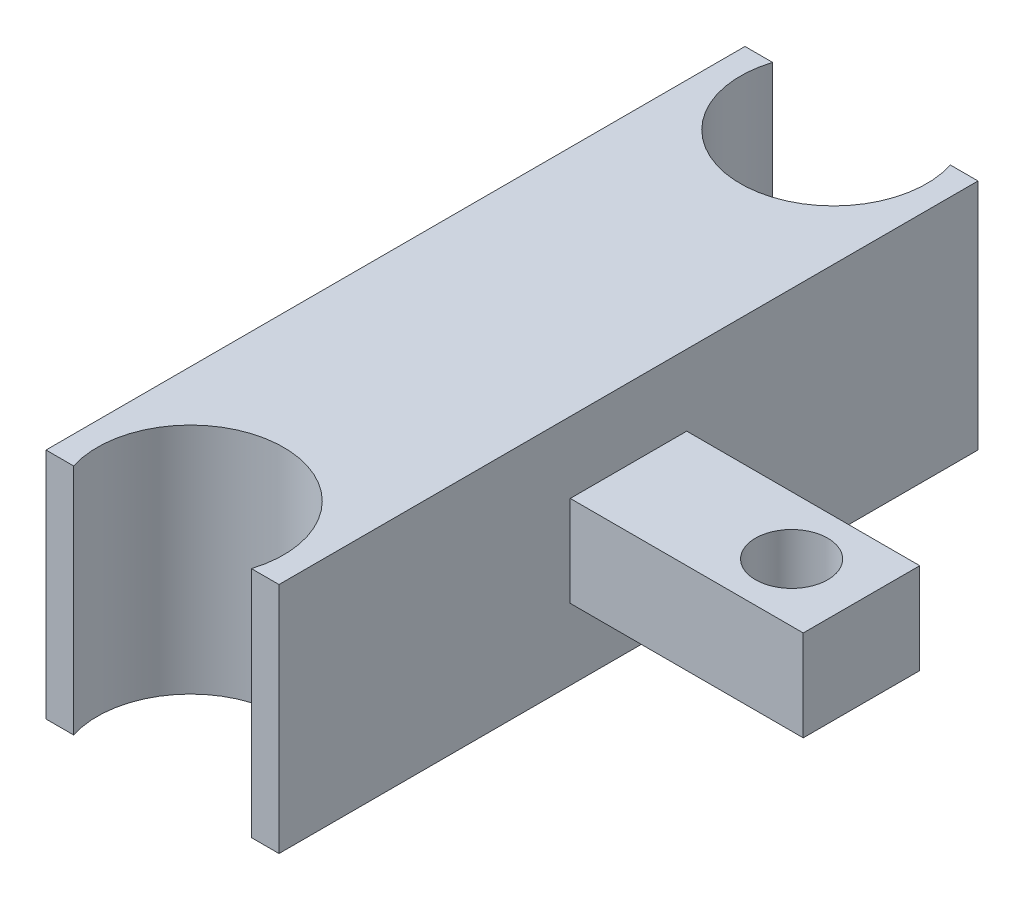
SolidWorks part; units mm, degrees
ref_plane "前视基准面" through (0, 0, 0) normal (0, 0, 1) x (1, 0, 0)
ref_plane "上视基准面" through (0, 0, 0) normal (0, 1, 0) x (1, 0, 0)
ref_plane "右视基准面" through (0, 0, 0) normal (1, 0, 0) x (0, 0, -1)
other "Configuration Table"
sketch "草图1" plane through (0, 0, 0) normal (0, 1, 0) x (1, 0, 0)
  line L1 (0, 0) -> (10, 0)
  line L2 (0, 0) -> (0, 5)
  line L3 (0, 5) -> (10, 5)
  line L4 (10, 0) -> (10, 5)
  circle A0 centre (7, 2.5) radius 1.55
  dimension "D4" = 3.1
  dimension "D1" = 5
  dimension "D2" = 10
  dimension "D3" = 3
  dimension "D5" = 2.5
extrude "凸台-拉伸1" add sketch "草图1" along normal blind 3.9 contours L2 L3 L4 L1
sketch "草图2" plane through (0, 0, 0) normal (-1, 0, 0) x (0, 0, 1)
  line L0 (-5, 3.9) -> (0, 0) construction
  line L1 (0, 3.9) -> (-5, 0) construction
  line L3 (12.5, -3.05) -> (-17.5, -3.05)
  line L4 (12.5, -3.05) -> (12.5, 6.95)
  line L5 (12.5, 6.95) -> (-17.5, 6.95)
  line L6 (-17.5, -3.05) -> (-17.5, 6.95)
  line L7 (12.5, -3.05) -> (-17.5, 6.95) construction
  line L8 (12.5, 6.95) -> (-17.5, -3.05) construction
  point P8 (-2.5, 1.95)
  dimension "D1" = 10
  dimension "D2" = 30
extrude "凸台-拉伸2" add sketch "草图2" along normal blind 10
sketch "草图3" plane through (0, 6.95, 0) normal (0, 1, 0) x (1, 0, 0)
  line L0 (-5, 17.5) -> (-5, -12.5) construction
  line L1 (-10, 17.5) -> (0, 17.5) construction
  line L2 (-10, -12.5) -> (0, -12.5) construction
  circle A0 centre (-5, 16.3) radius 4
  circle A1 centre (-5, -11.3) radius 4
  dimension "D2" = 8
  dimension "D3" = 8
  dimension "D1" = 1.2
  dimension "D4" = 1.2
extrude "切除-拉伸1" cut sketch "草图3" against normal blind 10 contours A0 | A1
